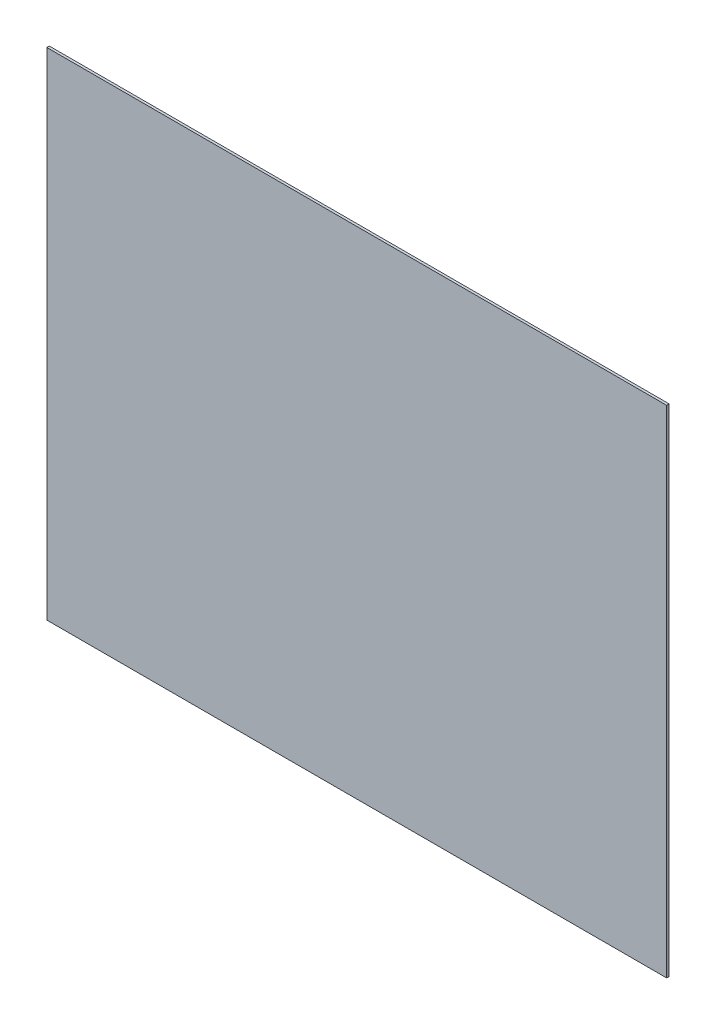
SolidWorks part; units mm, degrees
ref_plane "Front Plane" through (0, 0, 0) normal (0, 0, 1) x (1, 0, 0)
ref_plane "Top Plane" through (0, 0, 0) normal (0, 1, 0) x (1, 0, 0)
ref_plane "Right Plane" through (0, 0, 0) normal (1, 0, 0) x (0, 0, -1)
other "Configuration Table"
sketch "Sketch1" plane through (0, 0, 0) normal (0, 0, 1) x (1, 0, 0)
  line L1 (100, 300) -> (600, 300)
  line L2 (100, 300) -> (100, 700)
  line L3 (100, 700) -> (600, 700)
  line L4 (600, 300) -> (600, 700)
extrude "TOPPING_arka_duvar_pano_plakasi_1" add sketch "Sketch1" against normal blind 2 from offset 776 separate body
